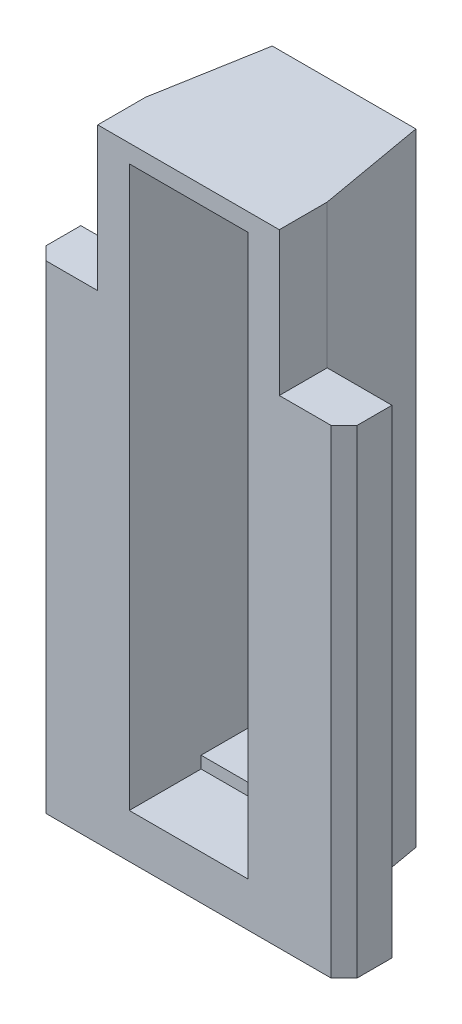
SolidWorks part; units mm, degrees
ref_plane "前视基准面" through (0, 0, 0) normal (0, 0, 1) x (1, 0, 0)
ref_plane "上视基准面" through (0, 0, 0) normal (0, 1, 0) x (1, 0, 0)
ref_plane "右视基准面" through (0, 0, 0) normal (1, 0, 0) x (0, 0, -1)
sketch "草图1" plane through (0, 0, 0) normal (0, 1, 0) x (1, 0, 0)
  line L0 (-13, 0) -> (13, 0)
  line L1 (13, 0) -> (13, 4)
  line L2 (13, 4) -> (7.5869, 4)
  line L3 (7.5869, 4) -> (6, 13)
  line L4 (6, 13) -> (-6, 13)
  line L5 (0, 13) -> (0, -8.0101) construction
  line L6 (-7.5869, 4) -> (-6, 13)
  line L7 (-13, 4) -> (-7.5869, 4)
  line L8 (-13, 0) -> (-13, 4)
  point P0 (9.7828, 2.8889)
  point P12 (0, 0)
  dimension "D1" = 26
  dimension "D2" = 12
  dimension "D3" = 13
  dimension "D4" = 4
  dimension "D5" = 100
extrude "凸台-拉伸1" add sketch "草图1" along normal blind 40
sketch "草图2" plane through (0, 40, 0) normal (0, 1, 0) x (1, 0, 0)
  line L0 (7.5869, 4) -> (6, 13) construction
  line L1 (6, 13) -> (-6, 13) construction
  line L2 (-6, 13) -> (-7.5869, 4) construction
  line L3 (7.5869, 4) -> (6, 13)
  line L4 (6, 13) -> (-6, 13)
  line L5 (-6, 13) -> (-7.5869, 4)
  line L6 (-7.5869, 4) -> (-7.5869, 0)
  line L7 (-13, 0) -> (13, 0) construction
  line L8 (-7.5869, 0) -> (7.5869, 0)
  line L9 (7.5869, 0) -> (7.5869, 4)
extrude "凸台-拉伸2" add sketch "草图2" along normal blind 12
chamfer "倒角1" distance 1.1 angle 45 2 edges at (13, 20, 0) (-13, 20, 0)
sketch "草图3" plane through (0, 0, 0) normal (0, 0, 1) x (1, 0, 0)
  line L0 (0, 0) -> (0, 27.35) construction
  line L1 (-11.9, 0) -> (11.9, 0) construction
  line L2 (-7.5869, 52) -> (7.5869, 52) construction
  line L3 (-4.95, 4.7) -> (4.95, 4.7)
  line L4 (-4.95, 4.7) -> (-4.95, 50)
  line L5 (-4.95, 50) -> (4.95, 50)
  line L6 (4.95, 4.7) -> (4.95, 50)
  line L7 (-4.95, 4.7) -> (4.95, 50) construction
  line L8 (-4.95, 50) -> (4.95, 4.7) construction
  point P8 (6.8786, 7.7362)
  point P9 (5.7519, 49.8378)
  point P10 (5.3368, 50.1936)
  dimension "D1" = 45.3
  dimension "D2" = 9.9
  dimension "D3" = 2
extrude "切除-拉伸1" cut sketch "草图3" against normal offset from surface (10 mm away) 3 up to face at (0, 26, -13)
sketch "草图4" plane through (0, 0, -10) normal (0, 0, 1) x (1, 0, 0)
  line L0 (0, 50) -> (0, 4.7) construction
  line L1 (-4.95, 50) -> (4.95, 50) construction
  line L2 (4.95, 4.7) -> (-4.95, 4.7) construction
  line L4 (-1.75, 9.85) -> (1.75, 9.85)
  line L5 (-1.75, 9.85) -> (-1.75, 44.85)
  line L6 (-1.75, 44.85) -> (1.75, 44.85)
  line L7 (1.75, 9.85) -> (1.75, 44.85)
  line L8 (-1.75, 9.85) -> (1.75, 44.85) construction
  line L9 (-1.75, 44.85) -> (1.75, 9.85) construction
  point P6 (0, 27.35)
  dimension "D1" = 35
  dimension "D2" = 3.5
extrude "切除-拉伸2" cut sketch "草图4" against normal through all
sketch "草图5" plane through (0, 0, 0) normal (0, 0, 1) x (1, 0, 0)
  line L0 (4.95, 50) -> (4.95, 4.7) construction
  line L1 (-4.95, 50) -> (4.95, 50)
  line L2 (-4.95, 50) -> (-4.95, 50.5)
  line L3 (-4.95, 50.5) -> (4.95, 50.5)
  line L4 (4.95, 50) -> (4.95, 50.5)
  line L5 (4.95, 4.7) -> (4.95, 50) construction
  line L7 (-4.95, 4.7) -> (4.95, 4.7)
  line L8 (-4.95, 4.7) -> (-4.95, 3.7)
  line L9 (-4.95, 3.7) -> (4.95, 3.7)
  line L10 (4.95, 4.7) -> (4.95, 3.7)
  point P5 (4.95, 4.7)
  dimension "D1" = 0.5
  dimension "D2" = 1
extrude "切除-拉伸3" cut sketch "草图5" against normal offset from surface (6 mm away) 4 up to face at (0, 27.35, -10)
sketch "草图6" plane through (0, 0, -10) normal (0, 0, 1) x (1, 0, 0)
  line L0 (1.75, 27.35) -> (19.3892, 27.35) construction
  line L1 (1.75, 9.85) -> (1.75, 44.85) construction
  line L2 (0, 44.85) -> (0, 9.85) construction
  line L3 (1.75, 44.85) -> (-1.75, 44.85) construction
  line L4 (-1.75, 9.85) -> (1.75, 9.85) construction
  circle A0 centre (0, 47.85) radius 1.15
  circle A1 centre (0, 6.85) radius 1.15
  point P12 (0, 47.85)
  dimension "D1" = 41
  dimension "D2" = 2.3
extrude "切除-拉伸4" cut sketch "草图6" against normal through all
sketch "草图7" plane through (0, 0, -13) normal (0, 0, -1) x (-1, 0, 0)
  circle A0 centre (0, 47.85) radius 1.95
  circle A1 centre (0, 6.85) radius 1.95
  dimension "D1" = 3.9
extrude "切除-拉伸5" cut sketch "草图7" against normal blind 1.2
